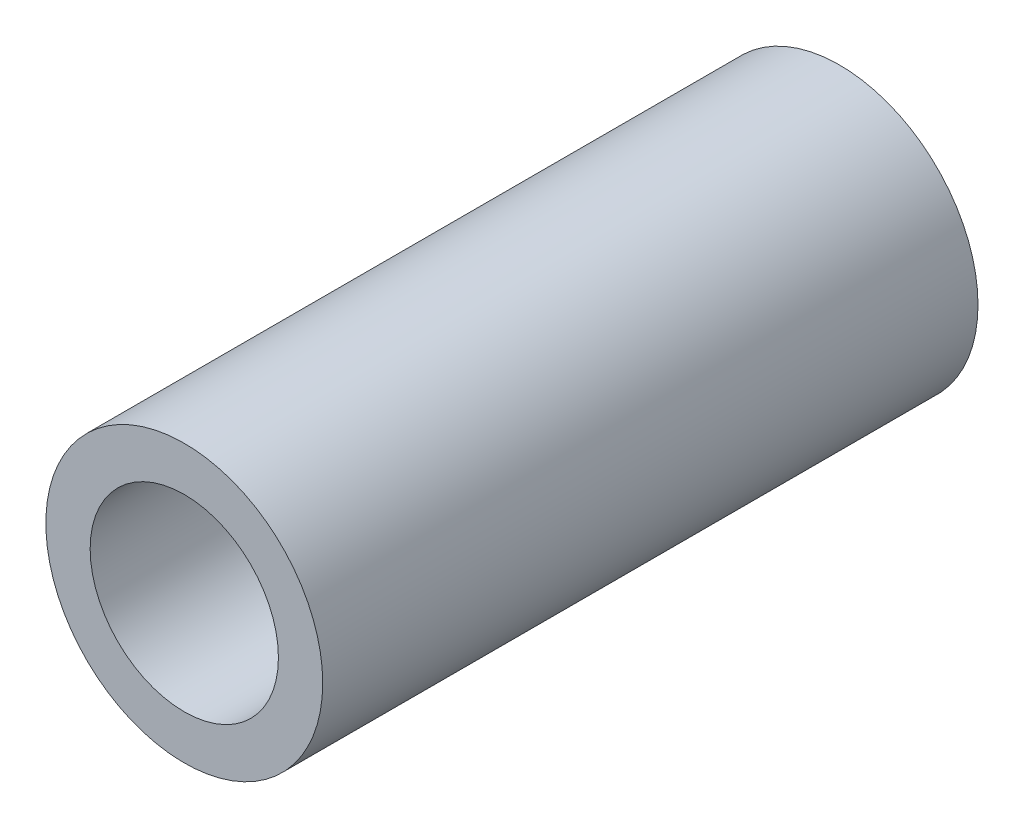
SolidWorks part; units mm, degrees
ref_plane "前视基准面" through (0, 0, 0) normal (0, 0, 1) x (1, 0, 0)
ref_plane "上视基准面" through (0, 0, 0) normal (0, 1, 0) x (1, 0, 0)
ref_plane "右视基准面" through (0, 0, 0) normal (1, 0, 0) x (0, 0, -1)
sketch "草图1" plane through (0, 0, 0) normal (0, 0, 1) x (1, 0, 0)
  circle A0 centre (0, 0) radius 5.1
  circle A1 centre (0, 0) radius 7.5
  dimension "D1" = 10.2
  dimension "D2" = 15
extrude "凸台-拉伸1" add sketch "草图1" along normal blind 35.5
